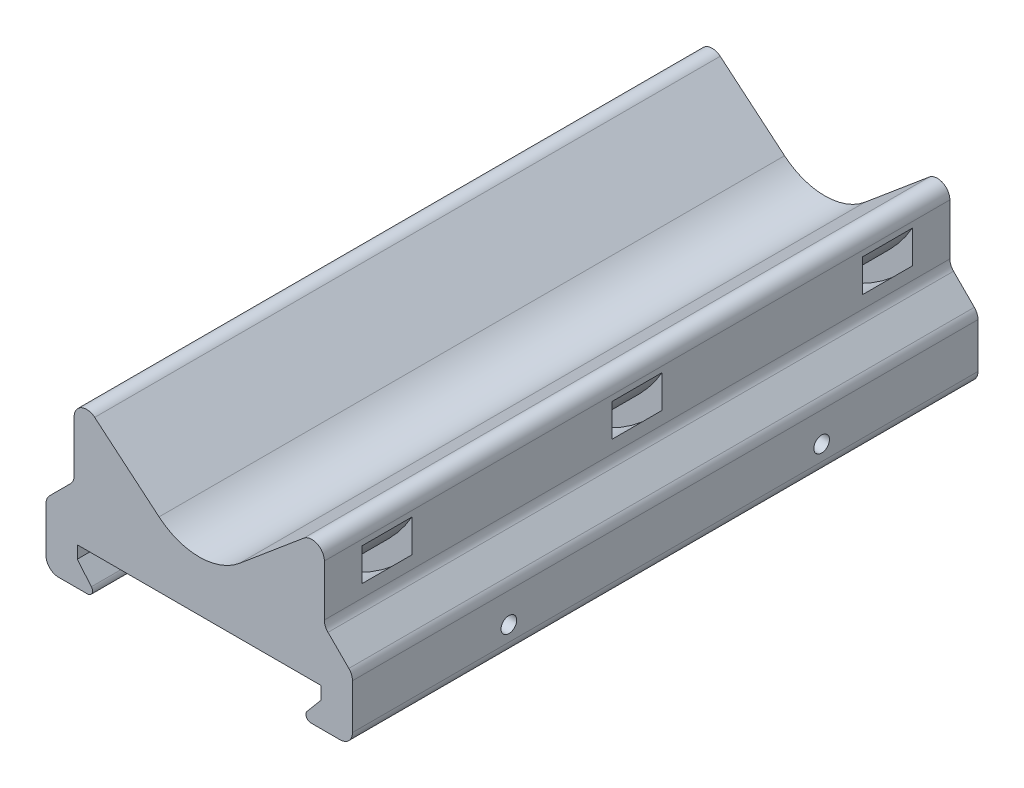
SolidWorks part; units mm, degrees
ref_plane "Front Plane" through (0, 0, 0) normal (0, 0, 1) x (1, 0, 0)
ref_plane "Top Plane" through (0, 0, 0) normal (0, 1, 0) x (1, 0, 0)
ref_plane "Right Plane" through (0, 0, 0) normal (1, 0, 0) x (0, 0, -1)
sketch "Sketch1" plane through (0, 0, 0) normal (0, 0, 1) x (1, 0, 0)
  line L0 (0, 15.6125) -> (0, -8.5333) construction
  line L1 (6.4279, 10.3936) -> (16.7144, 19.0251)
  line L2 (20, 17.493) -> (20, 9.3284)
  line L3 (20.5858, 7.9142) -> (23.9142, 4.5858)
  line L4 (24.5, 3.1716) -> (24.5, -4)
  line L5 (22.5, -6) -> (17.8592, -6)
  line L7 (19.5, 0) -> (-19.5, 0)
  line L9 (-22.5, -6) -> (-17.8592, -6)
  line L10 (-24.5, 3.1716) -> (-24.5, -4)
  line L11 (-20.5858, 7.9142) -> (-23.9142, 4.5858)
  line L12 (-20, 17.493) -> (-20, 9.3284)
  line L13 (-6.4279, 10.3936) -> (-16.7144, 19.0251)
  line L14 (-19.05, -0.1) -> (19.05, -0.1) construction
  line L15 (19.05, -0.1) -> (19.05, -2.1) construction
  line L16 (19.05, -2.1) -> (13.05, -8.1) construction
  line L17 (13.05, -8.1) -> (-13.05, -8.1) construction
  line L18 (-13.05, -8.1) -> (-19.05, -2.1) construction
  line L19 (-19.05, -0.1) -> (-19.05, -2.1) construction
  line L20 (17.2464, -4.6858) -> (19.5, -2)
  line L21 (19.5, -2) -> (19.5, 0)
  line L22 (-19.5, -2) -> (-19.5, 0)
  line L23 (-17.2464, -4.6858) -> (-19.5, -2)
  arc A0 (-6.4279, 10.3936) -> (6.4279, 10.3936) centre (0, 18.0541) ccw
  arc A1 (20, 9.3284) -> (20.5858, 7.9142) centre (22, 9.3284) ccw
  arc A2 (23.9142, 4.5858) -> (24.5, 3.1716) centre (22.5, 3.1716) cw
  arc A3 (24.5, -4) -> (22.5, -6) centre (22.5, -4) cw
  arc A4 (-22.5, -6) -> (-24.5, -4) centre (-22.5, -4) cw
  arc A5 (-24.5, 3.1716) -> (-23.9142, 4.5858) centre (-22.5, 3.1716) cw
  arc A6 (-20.5858, 7.9142) -> (-20, 9.3284) centre (-22, 9.3284) ccw
  arc A7 (16.7144, 19.0251) -> (20, 17.493) centre (18, 17.493) cw
  arc A8 (-20, 17.493) -> (-16.7144, 19.0251) centre (-18, 17.493) cw
  arc A9 (17.8592, -6) -> (17.2464, -4.6858) centre (17.8592, -5.2) cw
  arc A10 (-17.2464, -4.6858) -> (-17.8592, -6) centre (-17.8592, -5.2) cw
  point P11 (0, 0)
  point P19 (0, 5)
  point P22 (20, 8.5)
  point P25 (24.5, 4)
  point P28 (24.5, -6)
  point P31 (-24.5, -6)
  point P34 (-24.5, 4)
  point P37 (-20, 8.5)
  point P40 (20, 21.782)
  point P43 (-20, 21.782)
  point P51 (0, -8.1)
  point P52 (0, -0.1)
  point P56 (16.1436, -6)
  point P59 (-16.1436, -6)
  dimension "D10" = 10
  dimension "D11" = 2
  dimension "D18" = 0.8
  dimension "D1" = 19.5
  dimension "D2" = 5
  dimension "D3" = 20
  dimension "D4" = 135
  dimension "D5" = 50
  dimension "D6" = 6
  dimension "D7" = 4
  dimension "D8" = 50
  dimension "D9" = 5
  dimension "D12" = 38.1
  dimension "D13" = 135
  dimension "D14" = 8
  dimension "D15" = 2
  dimension "D16" = 0.2
  dimension "D17" = 2
extrude "Boss-Extrude1" add sketch "Sketch1" along normal blind 100
sketch "Sketch2" plane through (0, 0, 0) normal (1, 0, 0) x (0, 0, -1)
  line L0 (-100, 0) -> (0, 0) construction
  line L1 (-6, 5) -> (-14, 5)
  line L2 (-6, 5) -> (-6, 2)
  line L3 (-6, 2) -> (-14, 2)
  line L4 (-14, 5) -> (-14, 2)
  line L5 (0, 4.5858) -> (0, 7.9142) construction
  line L6 (-46, 5) -> (-54, 5)
  line L7 (-46, 5) -> (-46, 2)
  line L8 (-46, 2) -> (-54, 2)
  line L9 (-54, 5) -> (-54, 2)
  line L10 (-86, 5) -> (-94, 5)
  line L11 (-86, 5) -> (-86, 2)
  line L12 (-86, 2) -> (-94, 2)
  line L13 (-94, 5) -> (-94, 2)
  line L14 (-89.3538, 28.0541) -> (-4.4002, 28.0541) construction
  line L15 (-100, 8.0541) -> (0, 8.0541) construction
  dimension "D1" = 8
  dimension "D2" = 3
  dimension "D3" = 2
  dimension "D4" = 6
  dimension "D6" = 20
  dimension "D5" = 3
revolve "Cut-Revolve1" cut sketch "Sketch2" angle 360 about L14
hole_wizard "M3x0.5 Tapped Hole1" positions "Sketch3" profile "Sketch4" tap size "M3x0.5" standard "ANSI Metric" end condition through all
sketch "Sketch3" plane through (-24.5, 0, 0) normal (-1, 0, 0) x (0, 0, 1)
  line L0 (75, -1.5555) -> (25, -1.5555) construction
  point P0 (25, -1.5555)
  point P2 (75, -1.5555)
  point P10 (50, -1.5555)
  dimension "D1" = 50
  dimension "D2" = 50
sketch "Sketch4" plane through (-24.5, -1.5555, 25) normal (0, 1, 0) x (0, 0, 1)
  line L0 (0, 0) -> (0, 49)
  line L1 (0, 49) -> (1.25, 49)
  line L2 (1.25, 49) -> (1.25, 0.275)
  line L3 (1.25, 0.275) -> (1.525, 0)
  line L5 (1.525, 0) -> (0, 0)
  line L6 (-1.25, 0.275) -> (-1.525, 0) construction
  line L11 (0, -6.35) -> (0, 107.95) construction
  dimension "Thru Tap Drill Dia." = 2.5
  dimension "Thru Tap Drill Depth" = 49
  dimension "Near C'Sink Dia." = 3.05
  dimension "Near C'Sink Angle" = 90
cosmetic thread "Hole Thread1" parameters "D2"=3
cosmetic thread "Hole Thread2" parameters "D2"=3
